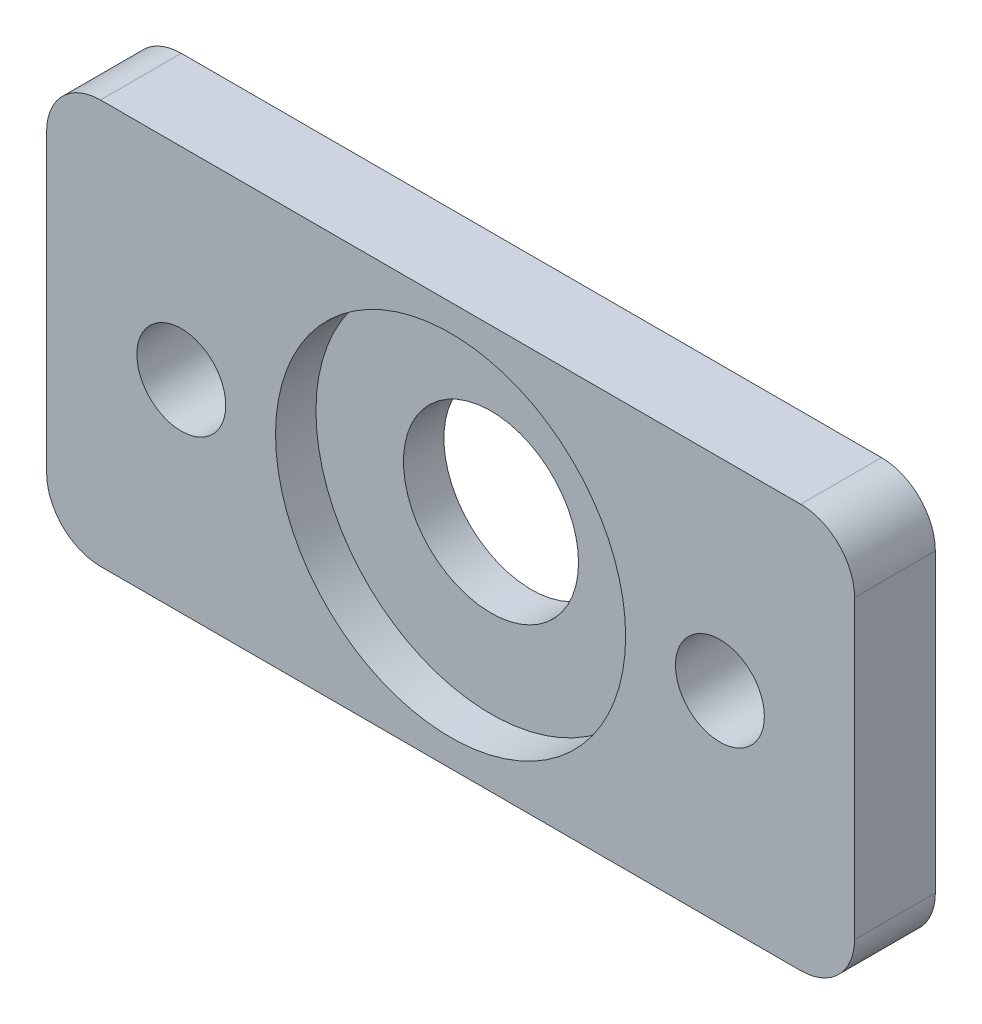
SolidWorks part; units mm, degrees
ref_plane "Спереди" through (0, 0, 0) normal (0, 0, 1) x (1, 0, 0)
ref_plane "Сверху" through (0, 0, 0) normal (0, 1, 0) x (1, 0, 0)
ref_plane "Справа" through (0, 0, 0) normal (1, 0, 0) x (0, 0, -1)
sketch "Эскиз1" plane through (0, 0, 0) normal (0, 0, 1) x (1, 0, 0)
  line L1 (2, 0) -> (28, 0)
  line L2 (0, 2) -> (0, 13)
  line L3 (2, 15) -> (28, 15)
  line L4 (30, 2) -> (30, 13)
  arc A0 (28, 15) -> (30, 13) centre (28, 13) cw
  arc A1 (28, 0) -> (30, 2) centre (28, 2) ccw
  arc A2 (2, 0) -> (0, 2) centre (2, 2) cw
  arc A3 (0, 13) -> (2, 15) centre (2, 13) cw
  point P9 (30, 0)
  point P12 (0, 0)
  point P15 (0, 15)
  dimension "D3" = 2
  dimension "D1" = 30
  dimension "D2" = 15
extrude "Бобышка-Вытянуть1" add sketch "Эскиз1" along normal blind 3
sketch "Эскиз2" plane through (0, 0, 3) normal (0, 0, 1) x (1, 0, 0)
  line L0 (28, 15) -> (2, 15) construction
  line L1 (30, 2) -> (30, 13) construction
  circle A0 centre (15, 7.5) radius 6.5
  point P4 (15, 15)
  point P7 (30, 7.5)
  dimension "D1" = 13
  dimension "D2" = 0
  dimension "D3" = 0
extrude "Вырез-Вытянуть1" cut sketch "Эскиз2" against normal blind 1.5
sketch "Эскиз3" plane through (0, 0, 3) normal (0, 0, 1) x (1, 0, 0)
  circle A0 centre (15, 7.5) radius 3.25
  dimension "D1" = 6.5
extrude "Вырез-Вытянуть2" cut sketch "Эскиз3" against normal through all
sketch "Эскиз4" plane through (0, 0, 3) normal (0, 0, 1) x (1, 0, 0)
  line L0 (0, 13) -> (0, 2) construction
  circle A0 centre (5, 7.5) radius 1.65
  circle A1 centre (15, 7.5) radius 3.25 construction
  circle A2 centre (25, 7.5) radius 1.65
  point P4 (0, 7.5)
  dimension "D1" = 3.3
  dimension "D2" = 0
  dimension "D3" = 10
  dimension "D4" = 2
extrude "Вырез-Вытянуть3" cut sketch "Эскиз4" against normal through all
